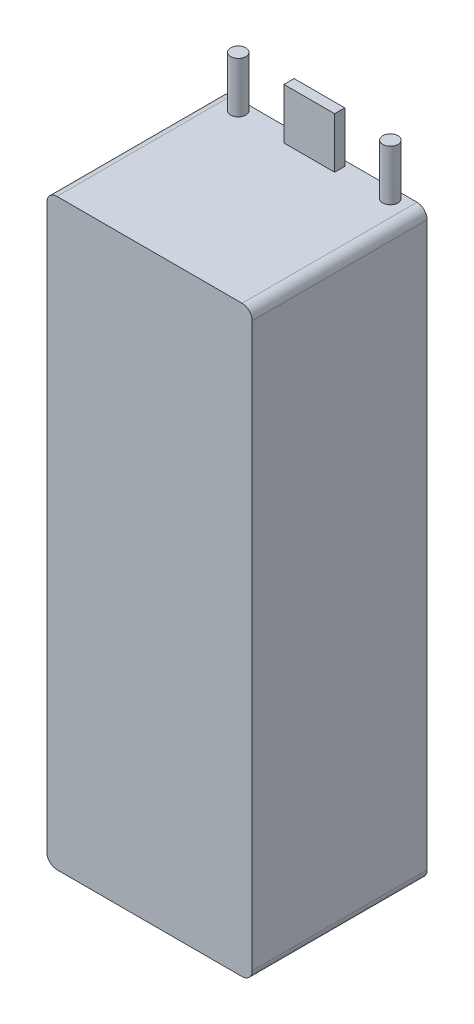
SolidWorks part; units mm, degrees
ref_plane "Front" through (0, 0, 0) normal (0, 0, 1) x (1, 0, 0)
ref_plane "Top" through (0, 0, 0) normal (0, 1, 0) x (1, 0, 0)
ref_plane "Right" through (0, 0, 0) normal (1, 0, 0) x (0, 0, -1)
sketch "Sketch1" plane through (0, 0, 0) normal (0, 1, 0) x (1, 0, 0)
  line L1 (-20.25, -17.25) -> (20.25, -17.25)
  line L2 (-20.25, -17.25) -> (-20.25, 17.25)
  line L3 (-20.25, 17.25) -> (20.25, 17.25)
  line L4 (20.25, -17.25) -> (20.25, 17.25)
  line L5 (-20.25, -17.25) -> (20.25, 17.25) construction
  line L6 (-20.25, 17.25) -> (20.25, -17.25) construction
  point P0 (0, 0)
  dimension "D1" = 40.5
  dimension "D2" = 34.5
extrude "Boss-Extrude1" add sketch "Sketch1" along normal blind 115
sketch "Sketch2" plane through (0, 115, 0) normal (0, 1, 0) x (1, 0, 0)
  line L0 (-20.25, 15.25) -> (20.25, 15.25) construction
  line L1 (-20.25, 17.25) -> (-20.25, -17.25) construction
  line L2 (20.25, -17.25) -> (20.25, 17.25) construction
  line L3 (20.25, 17.25) -> (-20.25, 17.25) construction
  line L4 (0, 17.25) -> (0, 1.3075) construction
  line L6 (-5, 16.25) -> (5, 16.25)
  line L7 (-5, 16.25) -> (-5, 14.25)
  line L8 (-5, 14.25) -> (5, 14.25)
  line L9 (5, 16.25) -> (5, 14.25)
  line L10 (-5, 16.25) -> (5, 14.25) construction
  line L11 (-5, 14.25) -> (5, 16.25) construction
  circle A0 centre (-15, 15.25) radius 1.5
  circle A2 centre (15, 15.25) radius 1.5
  point P14 (0, 15.25)
  dimension "D2" = 3
  dimension "D3" = 3
  dimension "D6" = 15
  dimension "D1" = 2
  dimension "D4" = 10
  dimension "D5" = 2
  dimension "D7" = 15
extrude "Boss-Extrude2" add sketch "Sketch2" along normal blind 10
fillet "Fillet1" radius 2 4 edges at (20.25, 115, 0) (-20.25, 115, 0) (20.25, 0, 0) (-20.25, 0, 0)
